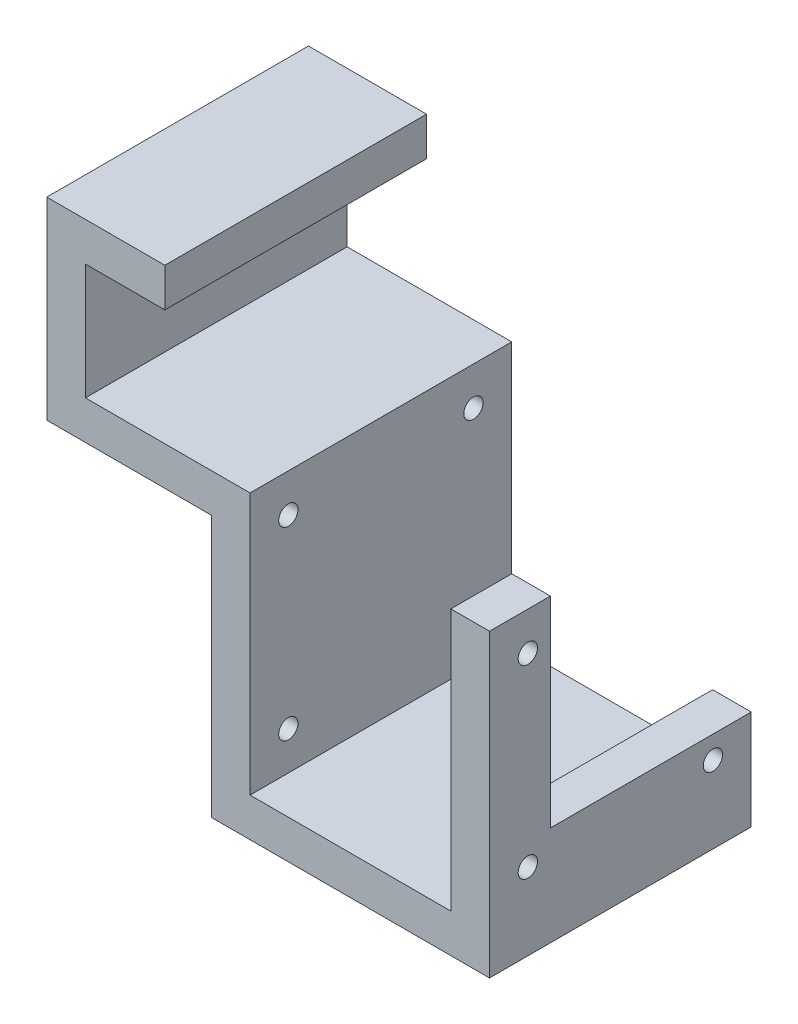
SolidWorks part; units mm, degrees
ref_plane "Front Plane" through (0, 0, 0) normal (0, 0, 1) x (1, 0, 0)
ref_plane "Top Plane" through (0, 0, 0) normal (0, 1, 0) x (1, 0, 0)
ref_plane "Right Plane" through (0, 0, 0) normal (1, 0, 0) x (0, 0, -1)
sketch "Sketch1" plane through (0, 0, 0) normal (0, 0, 1) x (1, 0, 0)
  line L0 (-6.35, -27.85) -> (-6.35, 15.15)
  line L1 (-6.35, 15.15) -> (-33.4, 15.15)
  line L2 (-33.4, 15.15) -> (-33.4, 46.9)
  line L3 (-33.4, 46.9) -> (-14, 46.9)
  line L4 (-14, 46.9) -> (-14, 40.55)
  line L5 (-14, 40.55) -> (-27.05, 40.55)
  line L6 (-27.05, 40.55) -> (-27.05, 21.5)
  line L7 (-27.05, 21.5) -> (0, 21.5)
  line L8 (0, 21.5) -> (0, -21.5)
  line L9 (0, -21.5) -> (33, -21.5)
  line L12 (33, -21.5) -> (33, -27.85)
  line L13 (33, -27.85) -> (-6.35, -27.85)
  line L14 (-27.05, 40.55) -> (11.05, 40.55) construction
  line L15 (-27.05, 40.55) -> (-33.4, 46.9) construction
  line L16 (-27.05, 21.5) -> (-33.4, 15.15) construction
  line L17 (-6.35, 15.15) -> (0, 21.5) construction
  line L18 (0, -21.5) -> (-6.35, -27.85) construction
  line L20 (-27.05, 21.5) -> (-27.05, 40.55) construction
  line L21 (-27.05, 21.5) -> (277.75, 21.5) construction
  line L22 (33, 18.9156) -> (33, -19.0795) construction
  line L23 (33, -21.5) -> (0, -21.5) construction
  line L25 (-14, 43.09) -> (-14, 48.9) construction
  dimension "D1" = 6.35
extrude "Boss-Extrude1" add sketch "Sketch1" against normal up to surface (43 mm away) contours L6 L7 L8 L9 L12 L13 L0 L1 L2 L3 L4 L5
sketch "Sketch2" plane through (33, 0, 0) normal (1, 0, 0) x (0, 0, -1)
  line L0 (43, -27.85) -> (0, -27.85) construction
  line L1 (33, -27.85) -> (43, -27.85)
  line L2 (33, -27.85) -> (33, 21.5)
  line L3 (33, 21.5) -> (43, 21.5)
  line L4 (43, -27.85) -> (43, 21.5)
  line L5 (33, -27.85) -> (43, 21.5) construction
  line L6 (33, 21.5) -> (43, -27.85) construction
  line L7 (43, 21.5) -> (0, 21.5) construction
  line L9 (0, -27.85) -> (33, -27.85)
  line L10 (0, -27.85) -> (0, -11.5)
  line L11 (0, -11.5) -> (33, -11.5)
  line L12 (33, -27.85) -> (33, -11.5)
  line L13 (0, -27.85) -> (33, -11.5) construction
  line L14 (0, -11.5) -> (33, -27.85) construction
  circle A0 centre (21.5, 0) radius 11.5 construction
  circle A2 centre (6.2942, -15.2058) radius 1.5
  circle A3 centre (36.7058, -15.2058) radius 1.5
  circle A4 centre (36.7058, 15.2058) radius 1.5
  circle A5 centre (6.2942, -15.2058) radius 1.5 construction
  point P4 (38, -3.175)
  point P17 (16.5, -19.675)
  line M5 (0, -27.85) -> (43, -27.85)
  line M6 (43, -27.85) -> (43, -21.5)
  line M7 (43, -21.5) -> (0, -21.5)
  line M8 (0, -21.5) -> (0, -27.85)
extrude "Boss-Extrude2" add sketch "Sketch2" along normal blind 6.35 contours L2 M5 M7 M8 | L11 L10 L2 A2 M7 | L2 M5 M6 M7 | L4 L3 L2 A4 A3 M7
sketch "Sketch3" plane through (-6.35, 0, 0) normal (1, 0, 0) x (0, 0, -1)
  line L0 (0, 15.2058) -> (6.2942, 15.2058) construction
  line L1 (0, 21.5) -> (0, -21.5) construction
  circle A0 centre (6.2942, -15.2058) radius 1.5875
  circle A1 centre (6.2942, 15.2058) radius 1.5875
  circle A8 centre (36.7058, 15.2058) radius 1.5875
  circle A9 centre (36.7058, -15.2058) radius 1.5875
  dimension "D1" = 3.175
extrude "Cut-Extrude1" cut sketch "Sketch3" against normal blind 12.7 and the other way through all
mirror "Mirror1" about plane through (0, 0, 0) normal (0, 0, 1) of bodies 103
delete or keep bodies "Body-Delete/Keep 1" type delete bodies bodies 103
